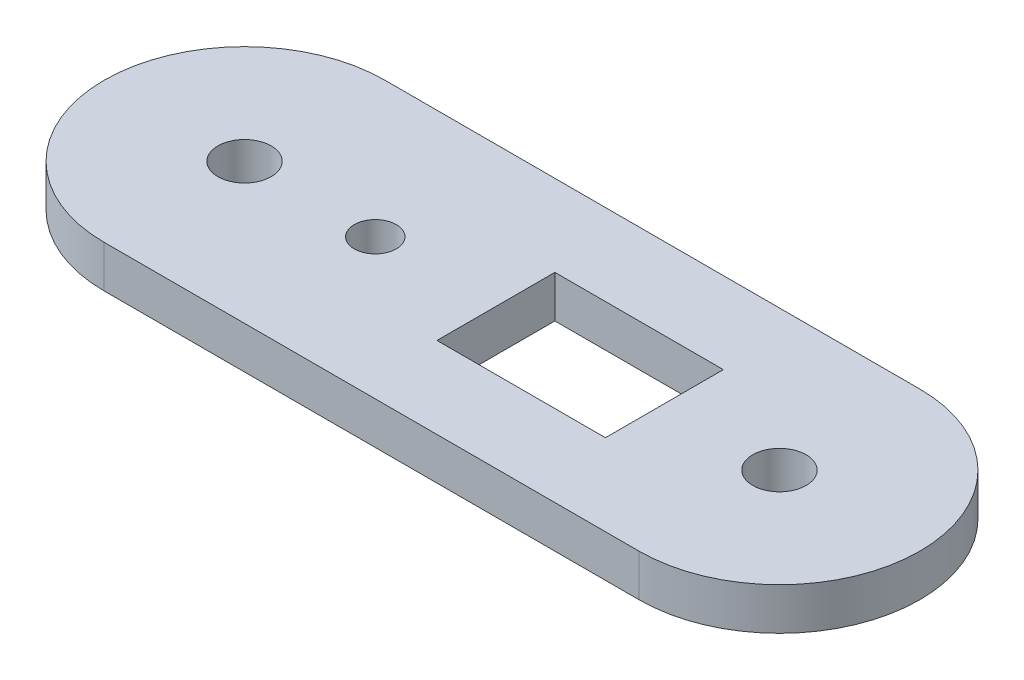
SolidWorks part; units mm, degrees
material "Acrylic (Medium-high impact)"
ref_plane "Front Plane" through (0, 0, 0) normal (0, 0, 1) x (1, 0, 0)
ref_plane "Top Plane" through (0, 0, 0) normal (0, 1, 0) x (1, 0, 0)
ref_plane "Right Plane" through (0, 0, 0) normal (1, 0, 0) x (0, 0, -1)
sketch "Sketch1" plane through (0, 0, 0) normal (0, 1, 0) x (1, 0, 0)
  line L0 (-19.05, 0) -> (19.05, 0) construction
  line L1 (-1.1452, -4.2) -> (10.8548, -4.2)
  line L2 (-1.1452, -4.2) -> (-1.1452, 4.2)
  line L3 (-1.1452, 4.2) -> (10.8548, 4.2)
  line L4 (10.8548, -4.2) -> (10.8548, 4.2)
  line L5 (-19.05, 0) -> (19.05, 0) construction
  line L6 (-19.05, 10) -> (19.05, 10)
  line L7 (-19.05, -10) -> (19.05, -10)
  circle A0 centre (-9.7377, 0) radius 1.5
  circle A1 centre (-19.05, 0) radius 1.9
  circle A2 centre (19.05, 0) radius 1.9
  arc A3 (-19.05, 10) -> (-19.05, -10) centre (-19.05, 0) ccw
  arc A4 (19.05, -10) -> (19.05, 10) centre (19.05, 0) ccw
  point P10 (0, 0)
  point P11 (-1.1452, 0)
  point P17 (10.8548, -4.2)
  point P18 (-9.7377, 0)
  dimension "D3" = 3
  dimension "D5" = 3.8
  dimension "D1" = 12
  dimension "D2" = 8.4
  dimension "D4" = 38.1
  dimension "D6" = 20
extrude "Boss-Extrude1" add sketch "Sketch1" along normal blind 3
